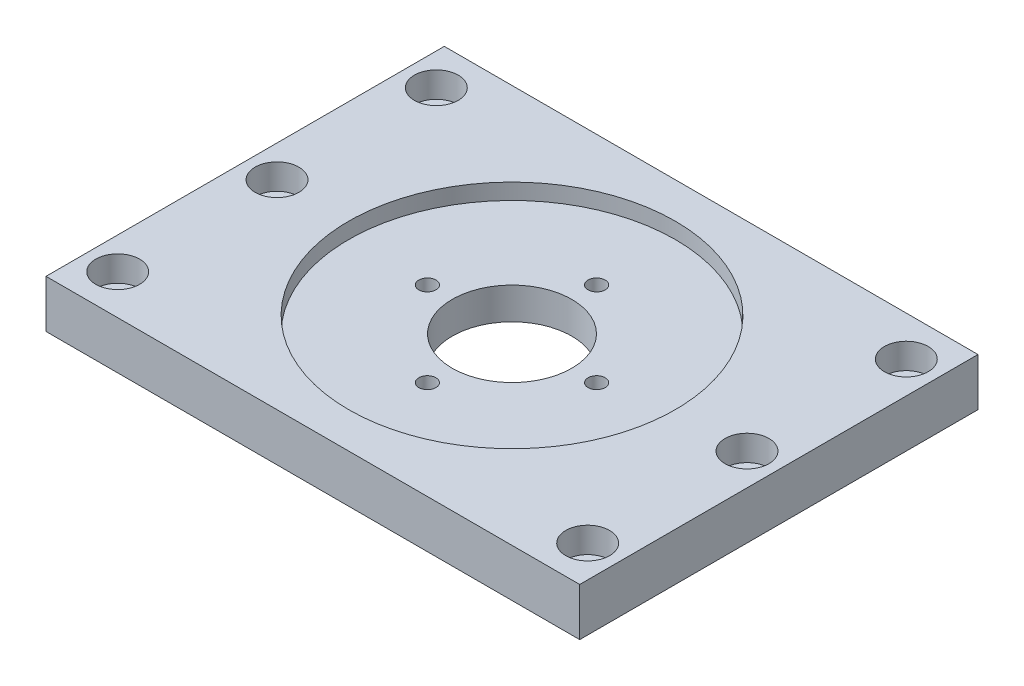
SolidWorks part; units mm, degrees
ref_plane "Front Plane" through (0, 0, 0) normal (0, 0, 1) x (1, 0, 0)
ref_plane "Top Plane" through (0, 0, 0) normal (0, 1, 0) x (1, 0, 0)
ref_plane "Right Plane" through (0, 0, 0) normal (1, 0, 0) x (0, 0, -1)
sketch "Sketch1" plane through (0, 0, 0) normal (0, 1, 0) x (1, 0, 0)
  line L1 (-67, -50) -> (67, -50)
  line L2 (-67, -50) -> (-67, 50)
  line L3 (-67, 50) -> (67, 50)
  line L4 (67, -50) -> (67, 50)
  line L5 (-67, -50) -> (67, 50) construction
  line L6 (-67, 50) -> (67, -50) construction
  point P0 (0, 0)
  dimension "D1" = 100
  dimension "D2" = 134
extrude "Boss-Extrude1" add sketch "Sketch1" along normal blind 12
sketch "Sketch2" plane through (0, 12, 0) normal (0, 1, 0) x (1, 0, 0)
  circle A0 centre (0, 0) radius 41
  dimension "D1" = 82
extrude "Cut-Extrude1" cut sketch "Sketch2" against normal blind 4
sketch "Sketch3" plane through (0, 8, 0) normal (0, 1, 0) x (1, 0, 0)
  circle A0 centre (0, 0) radius 15
  dimension "D1" = 30
extrude "Cut-Extrude2" cut sketch "Sketch3" against normal through all
hole_wizard "M4 Clearance Hole1" positions "Sketch4" profile "Sketch5" hole size "M4" standard "DIN"
sketch "Sketch4" plane through (0, 0, 0) normal (0, -1, 0) x (-1, 0, 0)
  circle A0 centre (0, 0) radius 21.25 construction
  point P7 (0, 21.25)
  point P12 (21.25, 0)
  point P13 (0, -21.25)
  point P14 (-21.25, 0)
  dimension "D1" = 42.5
  dimension "D2" = 4
sketch "Sketch5" plane through (21.25, 0, 0) normal (1, 0, 0) x (0, 0, -1)
  line L0 (0, 0) -> (0, 16.2919)
  line L1 (0, 16.2919) -> (2.15, 15)
  line L2 (2.15, 15) -> (2.15, 0)
  line L5 (2.15, 0) -> (0, 0)
  line L10 (0, 16.2919) -> (-2.15, 15) construction
  line L11 (0, -6.35) -> (0, 107.95) construction
  dimension "Hole Dia." = 4.3
  dimension "Hole Depth" = 15
  dimension "Drill Angle" = 118
hole_wizard "CBORE for M6 Hex Socket Head Cap Screw1" positions "Sketch6" profile "Sketch8" counterbore size "M6" standard "DIN"
sketch "Sketch6" plane through (0, 12, 0) normal (0, 1, 0) x (1, 0, 0)
  line L0 (59, 40) -> (67, 40) construction
  line L1 (67, -50) -> (67, 50) construction
  line L3 (-59, 40) -> (-67, 40) construction
  line L4 (-67, 50) -> (-67, -50) construction
  line L6 (59, 40) -> (59, 50) construction
  line L7 (67, 50) -> (-67, 50) construction
  line L9 (59, -40) -> (59, -50) construction
  line L10 (-67, -50) -> (67, -50) construction
  point P0 (59, 40)
  point P16 (-59, 40)
  point P17 (-59, 0)
  point P18 (-59, -40)
  point P19 (59, 0)
  point P20 (59, -40)
  dimension "D3" = 8
  dimension "D2" = 2
  dimension "D1" = 3
sketch "Sketch8" plane through (59, 12, -40) normal (1, 0, 0) x (0, 0, 1)
  line L0 (0, 0) -> (0, 16.9828)
  line L1 (0, 16.9828) -> (3.3, 15)
  line L2 (3.3, 15) -> (3.3, 6.4)
  line L3 (3.3, 6.4) -> (5.5, 6.4)
  line L4 (5.5, 6.4) -> (5.5, 0)
  line L5 (5.5, 0) -> (0, 0)
  line L10 (0, 16.9828) -> (-3.3, 15) construction
  line L11 (0, -6.35) -> (0, 107.95) construction
  dimension "Hole Dia." = 6.6
  dimension "Hole Depth" = 15
  dimension "C'Bore Dia." = 11
  dimension "C'Bore Depth" = 6.4
  dimension "Drill Angle" = 118
